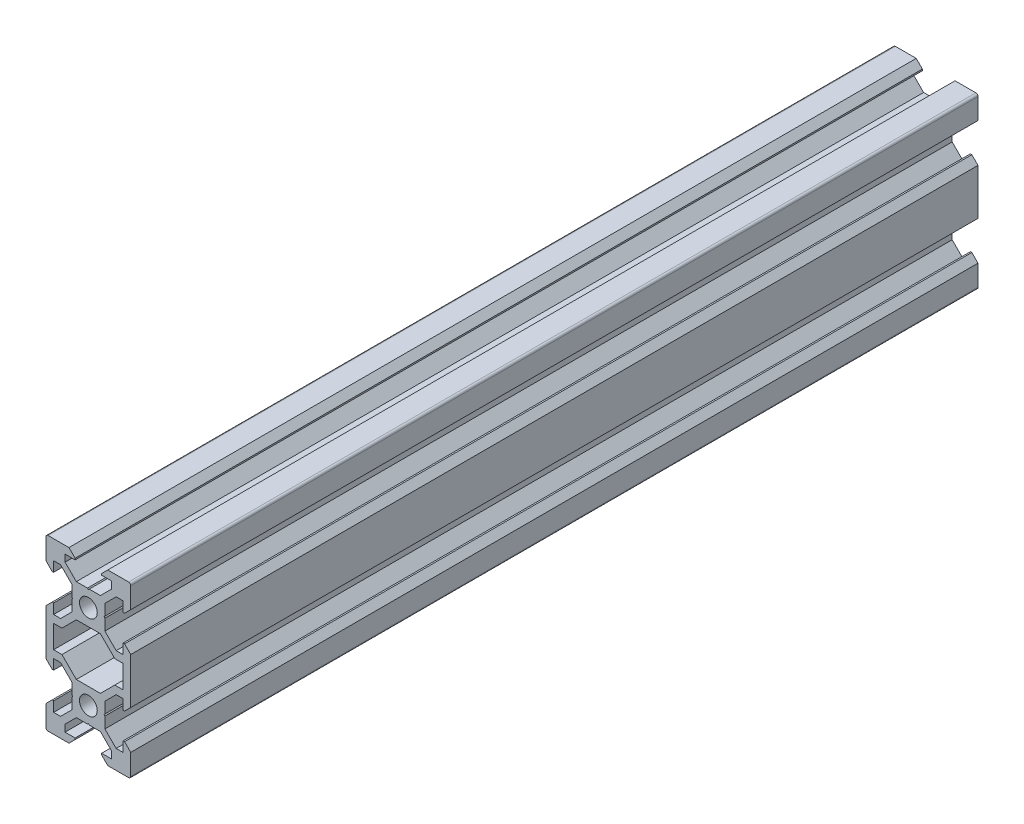
SolidWorks part; units mm, degrees
ref_plane "Front Plane" through (0, 0, 0) normal (0, 0, 1) x (1, 0, 0)
ref_plane "Top Plane" through (0, 0, 0) normal (0, 1, 0) x (1, 0, 0)
ref_plane "Right Plane" through (0, 0, 0) normal (1, 0, 0) x (0, 0, -1)
sketch "Sketch2" plane through (0, 0, 0) normal (0, 0, 1) x (1, 0, 0)
  line L106 (-6.1325, -2.3442) -> (-2.7325, -5.7442)
  line L107 (-8.0932, -2.3442) -> (-6.1325, -2.3442)
  line L108 (-8.0932, -2.3442) -> (-8.0932, 3.0558)
  line L109 (-8.0932, 3.0558) -> (-6.1325, 3.0558)
  line L110 (-6.1325, 3.0558) -> (-2.7325, 6.4558)
  line L111 (-2.7325, 6.4558) -> (2.9461, 6.4558)
  line L112 (6.3461, 3.0558) -> (2.9461, 6.4558)
  line L113 (8.3068, 3.0558) -> (6.3461, 3.0558)
  line L114 (8.3068, -2.3442) -> (8.3068, 3.0558)
  line L115 (8.3068, -2.3442) -> (6.3461, -2.3442)
  line L116 (6.3461, -2.3442) -> (2.9461, -5.7442)
  line L117 (-2.7325, -5.7442) -> (2.9461, -5.7442)
  line L118 (4.0068, 10.1458) -> (3.7968, 10.3558)
  line L119 (3.7968, 10.3558) -> (4.0068, 10.5658)
  line L120 (4.0068, 10.5658) -> (4.0068, 13.1951)
  line L121 (4.0068, 13.1951) -> (6.6675, 15.8558)
  line L122 (6.6675, 15.8558) -> (8.3068, 15.8558)
  line L123 (8.3068, 15.8558) -> (8.3068, 13.4808)
  line L124 (8.3068, 13.4808) -> (8.6518, 13.4808)
  line L125 (8.6518, 13.4808) -> (10.1068, 14.9358)
  line L126 (10.1068, 14.9358) -> (10.1068, 19.8558)
  line L127 (9.6068, 20.3558) -> (4.6868, 20.3558)
  line L128 (4.6868, 20.3558) -> (3.2318, 18.9008)
  line L129 (3.2318, 18.9008) -> (3.2318, 18.5558)
  line L130 (3.2318, 18.5558) -> (5.6068, 18.5558)
  line L131 (5.6068, 18.5558) -> (5.6068, 16.9165)
  line L132 (5.6068, 16.9165) -> (2.9461, 14.2558)
  line L133 (2.9461, 14.2558) -> (0.3168, 14.2558)
  line L134 (0.3168, 14.2558) -> (0.1068, 14.0458)
  line L135 (0.1068, 14.0458) -> (-0.1032, 14.2558)
  line L136 (-0.1032, 14.2558) -> (-2.7325, 14.2558)
  line L137 (-2.7325, 14.2558) -> (-5.3932, 16.9165)
  line L138 (-5.3932, 16.9165) -> (-5.3932, 18.5558)
  line L139 (-5.3932, 18.5558) -> (-3.0182, 18.5558)
  line L140 (-3.0182, 18.5558) -> (-3.0182, 18.9008)
  line L141 (-3.0182, 18.9008) -> (-4.4732, 20.3558)
  line L142 (-4.4732, 20.3558) -> (-9.3932, 20.3558)
  line L143 (-9.8932, 19.8558) -> (-9.8932, 14.9358)
  line L144 (-9.8932, 14.9358) -> (-8.4382, 13.4808)
  line L145 (-8.4382, 13.4808) -> (-8.0932, 13.4808)
  line L146 (-8.0932, 13.4808) -> (-8.0932, 15.8558)
  line L147 (-8.0932, 15.8558) -> (-6.4539, 15.8558)
  line L148 (-6.4539, 15.8558) -> (-3.7932, 13.1951)
  line L149 (-3.7932, 13.1951) -> (-3.7932, 10.5658)
  line L150 (-3.7932, 10.5658) -> (-3.5832, 10.3558)
  line L151 (-3.5832, 10.3558) -> (-3.7932, 10.1458)
  line L152 (-3.7932, 10.1458) -> (-3.7932, 7.5165)
  line L153 (-3.7932, 7.5165) -> (-6.4539, 4.8558)
  line L154 (-6.4539, 4.8558) -> (-8.0932, 4.8558)
  line L155 (-8.0932, 4.8558) -> (-8.0932, 7.2308)
  line L156 (-8.0932, 7.2308) -> (-8.4382, 7.2308)
  line L157 (-8.4382, 7.2308) -> (-9.8932, 5.7758)
  line L158 (-9.8932, 5.7758) -> (-9.8932, -5.0642)
  line L159 (-9.8932, -5.0642) -> (-8.4382, -6.5192)
  line L160 (-8.4382, -6.5192) -> (-8.0932, -6.5192)
  line L161 (-8.0932, -6.5192) -> (-8.0932, -4.1442)
  line L162 (-8.0932, -4.1442) -> (-6.4539, -4.1442)
  line L163 (-6.4539, -4.1442) -> (-3.7932, -6.8049)
  line L164 (-3.7932, -6.8049) -> (-3.7932, -9.4342)
  line L165 (-3.7932, -9.4342) -> (-3.5832, -9.6442)
  line L166 (-3.5832, -9.6442) -> (-3.7932, -9.8542)
  line L167 (-3.7932, -9.8542) -> (-3.7932, -12.4835)
  line L168 (-3.7932, -12.4835) -> (-6.4539, -15.1442)
  line L169 (-6.4539, -15.1442) -> (-8.0932, -15.1442)
  line L170 (-8.0932, -15.1442) -> (-8.0932, -12.7692)
  line L171 (-8.0932, -12.7692) -> (-8.4382, -12.7692)
  line L172 (-8.4382, -12.7692) -> (-9.8932, -14.2242)
  line L173 (-9.8932, -14.2242) -> (-9.8932, -19.1442)
  line L174 (-9.3932, -19.6442) -> (-4.4732, -19.6442)
  line L175 (-4.4732, -19.6442) -> (-3.0182, -18.1892)
  line L176 (-3.0182, -18.1892) -> (-3.0182, -17.8442)
  line L177 (-3.0182, -17.8442) -> (-5.3932, -17.8442)
  line L178 (-5.3932, -17.8442) -> (-5.3932, -16.2049)
  line L179 (-5.3932, -16.2049) -> (-2.7325, -13.5442)
  line L180 (-2.7325, -13.5442) -> (-0.1032, -13.5442)
  line L181 (-0.1032, -13.5442) -> (0.1068, -13.3342)
  line L182 (0.1068, -13.3342) -> (0.3168, -13.5442)
  line L183 (0.3168, -13.5442) -> (2.9461, -13.5442)
  line L184 (2.9461, -13.5442) -> (5.6068, -16.2049)
  line L185 (5.6068, -16.2049) -> (5.6068, -17.8442)
  line L186 (5.6068, -17.8442) -> (3.2318, -17.8442)
  line L187 (3.2318, -17.8442) -> (3.2318, -18.1892)
  line L188 (3.2318, -18.1892) -> (4.6868, -19.6442)
  line L189 (4.6868, -19.6442) -> (9.6068, -19.6442)
  line L190 (10.1068, -19.1442) -> (10.1068, -14.2242)
  line L191 (10.1068, -14.2242) -> (8.6518, -12.7692)
  line L192 (8.6518, -12.7692) -> (8.3068, -12.7692)
  line L193 (8.3068, -12.7692) -> (8.3068, -15.1442)
  line L194 (8.3068, -15.1442) -> (6.6675, -15.1442)
  line L195 (6.6675, -15.1442) -> (4.0068, -12.4835)
  line L196 (4.0068, -12.4835) -> (4.0068, -9.8542)
  line L197 (4.0068, -9.8542) -> (3.7968, -9.6442)
  line L198 (3.7968, -9.6442) -> (4.0068, -9.4342)
  line L199 (4.0068, -9.4342) -> (4.0068, -6.8049)
  line L200 (4.0068, -6.8049) -> (6.6675, -4.1442)
  line L201 (6.6675, -4.1442) -> (8.3068, -4.1442)
  line L202 (8.3068, -4.1442) -> (8.3068, -6.5192)
  line L203 (8.3068, -6.5192) -> (8.6518, -6.5192)
  line L204 (8.6518, -6.5192) -> (10.1068, -5.0642)
  line L205 (10.1068, -5.0642) -> (10.1068, 5.7758)
  line L206 (10.1068, 5.7758) -> (8.6518, 7.2308)
  line L207 (8.6518, 7.2308) -> (8.3068, 7.2308)
  line L208 (8.3068, 7.2308) -> (8.3068, 4.8558)
  line L209 (8.3068, 4.8558) -> (6.6675, 4.8558)
  line L210 (6.6675, 4.8558) -> (4.0068, 7.5165)
  line L211 (4.0068, 7.5165) -> (4.0068, 10.1458)
  circle A4 centre (0.1068, -9.6442) radius 2.1
  circle A5 centre (0.1068, 10.3558) radius 2.1
  arc A6 (10.1068, 19.8558) -> (9.6068, 20.3558) centre (9.6068, 19.8558) ccw
  arc A7 (-9.3932, 20.3558) -> (-9.8932, 19.8558) centre (-9.3932, 19.8558) ccw
  arc A8 (-9.8932, -19.1442) -> (-9.3932, -19.6442) centre (-9.3932, -19.1442) ccw
  arc A9 (9.6068, -19.6442) -> (10.1068, -19.1442) centre (9.6068, -19.1442) ccw
extrude "Boss-Extrude1" add sketch "Sketch2" along normal blind 200
